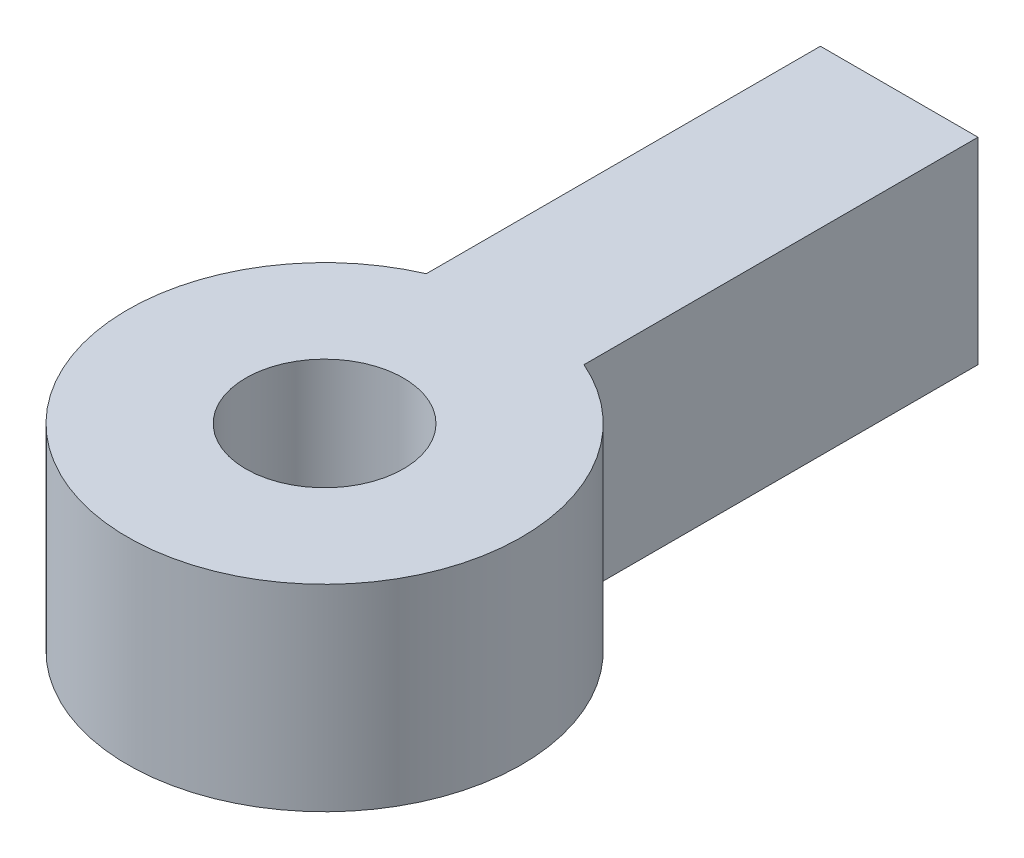
SolidWorks part; units mm, degrees
ref_plane "Front Plane" through (0, 0, 0) normal (0, 0, 1) x (1, 0, 0)
ref_plane "Top Plane" through (0, 0, 0) normal (0, 1, 0) x (1, 0, 0)
ref_plane "Right Plane" through (0, 0, 0) normal (1, 0, 0) x (0, 0, -1)
sketch "Sketch1" plane through (0, 0, 0) normal (0, 1, 0) x (1, 0, 0)
  line L0 (0, -12.973) -> (0, 29.2693) construction
  line L1 (-2, 14.5826) -> (2, 14.5826)
  line L2 (2, 14.5826) -> (2, 4.5826)
  line L3 (-2, 14.5826) -> (-2, 4.5826)
  arc A0 (-2, 4.5826) -> (2, 4.5826) centre (0, 0) ccw
  circle A1 centre (0, 0) radius 2
  point P8 (0, 14.5826)
  dimension "D1" = 10
  dimension "D4" = 4
  dimension "D2" = 10
  dimension "D3" = 2
extrude "Boss-Extrude1" add sketch "Sketch1" along normal blind 5
sketch "Sketch2" plane through (0, 5, 0) normal (0, 1, 0) x (1, 0, 0)
  circle A0 centre (0, 0) radius 2.5
  dimension "D1" = 5
